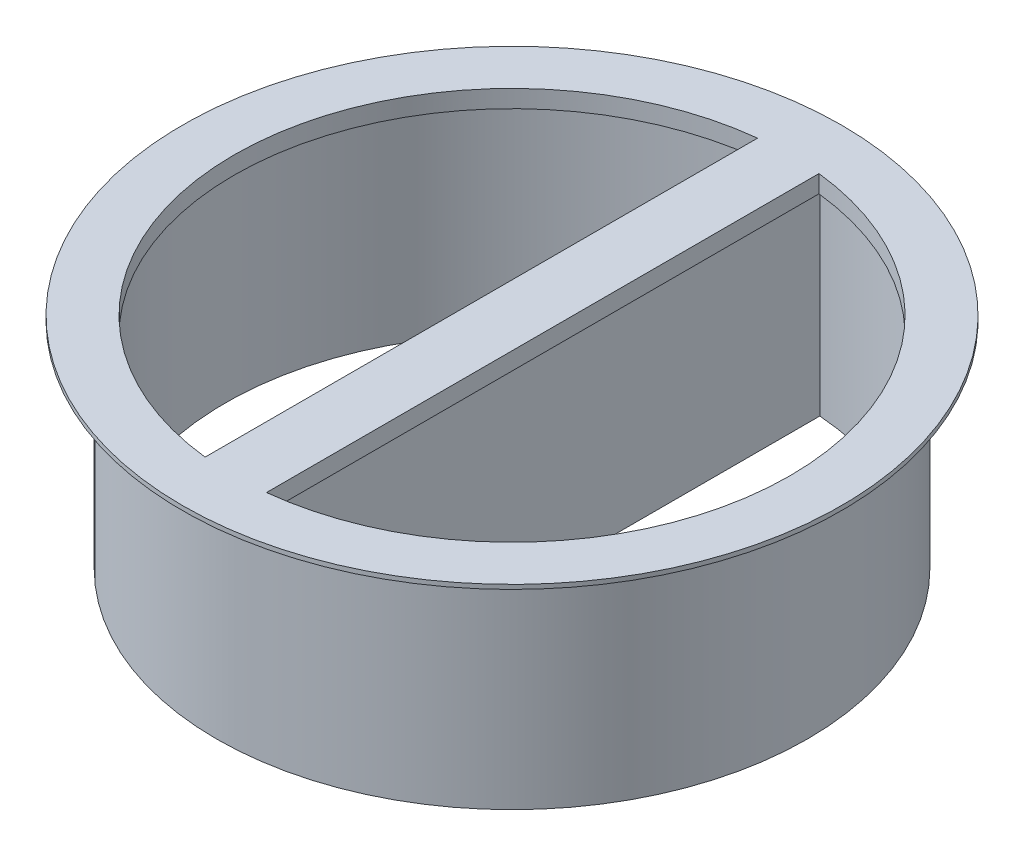
SolidWorks part; units mm, degrees
material "Rubber"
ref_plane "Front Plane" through (0, 0, 0) normal (0, 0, 1) x (1, 0, 0)
ref_plane "Top Plane" through (0, 0, 0) normal (0, 1, 0) x (1, 0, 0)
ref_plane "Right Plane" through (0, 0, 0) normal (1, 0, 0) x (0, 0, -1)
sketch "Outer Base Circle Sketch" plane through (0, 0, 0) normal (0, 1, 0) x (1, 0, 0)
  circle A0 centre (0, 0) radius 37.585
  dimension "D1" = 75.17
extrude "Body Extrude" add sketch "Outer Base Circle Sketch" along normal blind 25
sketch "Inner Base Circle Sketch" plane through (0, 0, 0) normal (0, -1, 0) x (1, 0, 0)
  circle A0 centre (0, 0) radius 33.7
  dimension "D1" = 67.4
extrude "Outer Body Extrude" cut sketch "Inner Base Circle Sketch" against normal blind 24.5 flip side to cut
sketch "Delivery Hole Sketch" plane through (0, 25, 0) normal (0, 1, 0) x (1, 0, 0)
  line L1 (-3.5, 31.5062) -> (-3.5, -31.5062)
  line L2 (3.5, 31.5062) -> (3.5, -31.5062)
  arc A0 (-3.5, 31.5062) -> (-3.5, -31.5062) centre (0, 0) ccw
  arc A1 (3.5, -31.5062) -> (3.5, 31.5062) centre (0, 0) ccw
  dimension "D1" = 63.4
  dimension "D2" = 3.5
extrude "Delivery Hole Extrude" cut sketch "Delivery Hole Sketch" against normal through all
sketch "Fastener Sketch" plane through (0, 0, 0) normal (0, -1, 0) x (1, 0, 0)
  line L1 (-2.5, 32.6043) -> (-2.5, -32.6043)
  line L2 (2.5, 32.6043) -> (2.5, -32.6043)
  arc A0 (-2.5, 32.6043) -> (-2.5, -32.6043) centre (0, 0) ccw
  arc A1 (2.5, -32.6043) -> (2.5, 32.6043) centre (0, 0) ccw
  dimension "D1" = 65.4
  dimension "D2" = 2.5
  dimension "D3" = 2.5
extrude "Fastener Extrude" cut sketch "Fastener Sketch" against normal blind 23
